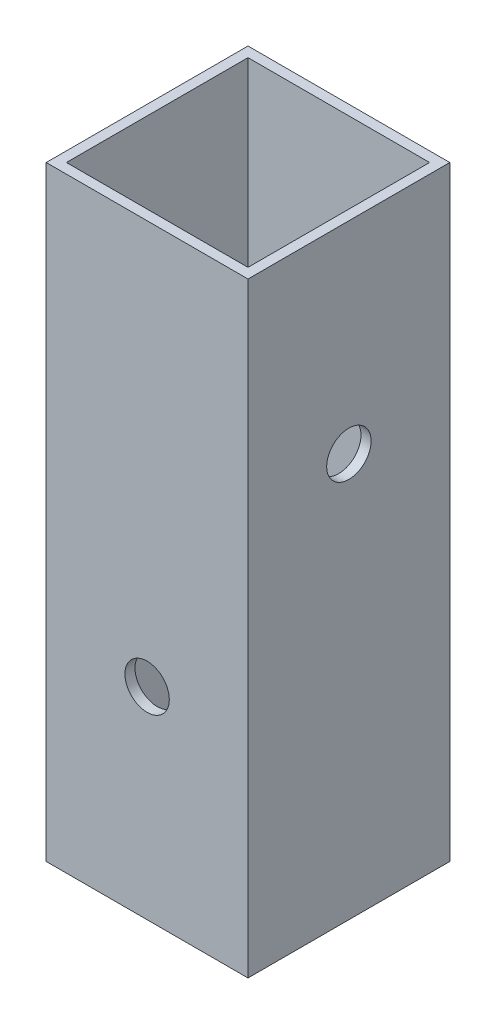
SolidWorks part; units mm, degrees
ref_plane "前视基准面" through (0, 0, 0) normal (0, 0, 1) x (1, 0, 0)
ref_plane "上视基准面" through (0, 0, 0) normal (0, 1, 0) x (1, 0, 0)
ref_plane "右视基准面" through (0, 0, 0) normal (1, 0, 0) x (0, 0, -1)
sketch "草图1" plane through (0, 0, 0) normal (0, 1, 0) x (1, 0, 0)
  line L2 (10, 0) -> (10, 10)
  line L3 (0, 10) -> (10, 10)
  line L6 (9, 0) -> (9, 9)
  line L7 (0, 9) -> (9, 9)
  line L8 (0, -10) -> (10, -10)
  line L9 (10, 0) -> (10, -10)
  line L10 (0, -9) -> (9, -9)
  line L11 (9, 0) -> (9, -9)
  line L12 (-10, 0) -> (-10, -10)
  line L13 (0, -10) -> (-10, -10)
  line L14 (-9, 0) -> (-9, -9)
  line L15 (0, -9) -> (-9, -9)
  line L16 (0, 10) -> (-10, 10)
  line L17 (-10, 0) -> (-10, 10)
  line L18 (0, 9) -> (-9, 9)
  line L19 (-9, 0) -> (-9, 9)
  point P27 (0, 0)
extrude "凸台-拉伸1" add sketch "草图1" against normal blind 280
sketch "草图2" plane through (0, 0, 10) normal (0, 0, 1) x (1, 0, 0)
  circle A0 centre (0, -40) radius 2.2
  circle A1 centre (0, -80) radius 2.2
  circle A2 centre (0, -120) radius 2.2
  circle A3 centre (0, -180) radius 2.2
  circle A4 centre (0, -220) radius 2.2
  circle A5 centre (0, -260) radius 2.2
  dimension "D1" = 3
  dimension "D2" = 2
  dimension "D3" = 3
extrude "切除-拉伸1" cut sketch "草图2" against normal blind 280
sketch "草图3" plane through (10, 0, 0) normal (1, 0, 0) x (0, 0, -1)
  circle A0 centre (0, -60) radius 2.2
  circle A1 centre (0, -100) radius 2.2
  circle A2 centre (0, -150) radius 2.2
  circle A3 centre (0, -200) radius 2.2
  circle A4 centre (0, -240) radius 2.2
extrude "切除-拉伸2" cut sketch "草图3" against normal blind 20
sketch "草图4" plane through (0, 0, 10) normal (0, 0, 1) x (1, 0, 0)
  line L0 (0, -220) -> (10, -220)
  line L1 (10, -280) -> (10, 0) construction
  line L2 (10, -220) -> (10, 0)
  line L3 (10, 0) -> (-10, 0)
  line L4 (-10, 0) -> (-10, -220)
  line L5 (-10, -280) -> (-10, 0) construction
  line L6 (-10, -220) -> (0, -220)
extrude "切除-拉伸3" cut sketch "草图4" against normal blind 59
sketch "草图5" plane through (0, 0, 10) normal (0, 0, 1) x (1, 0, 0)
  line L0 (-2.2, -220) -> (2.2, -220)
  arc A0 (-2.2, -220) -> (2.2, -220) centre (0, -220) ccw
extrude "凸台-拉伸3" add sketch "草图5" against normal blind 20
sketch "草图6" plane through (0, -220, 0) normal (0, 1, 0) x (1, 0, 0)
  line L0 (-2.2, 9) -> (2.2, 9)
  line L1 (-2.2, 9) -> (-2.2, -9)
  line L2 (2.2, 9) -> (2.2, -9)
  line L3 (-2.2, -9) -> (2.2, -9)
extrude "切除-拉伸4" cut sketch "草图6" against normal blind 20
